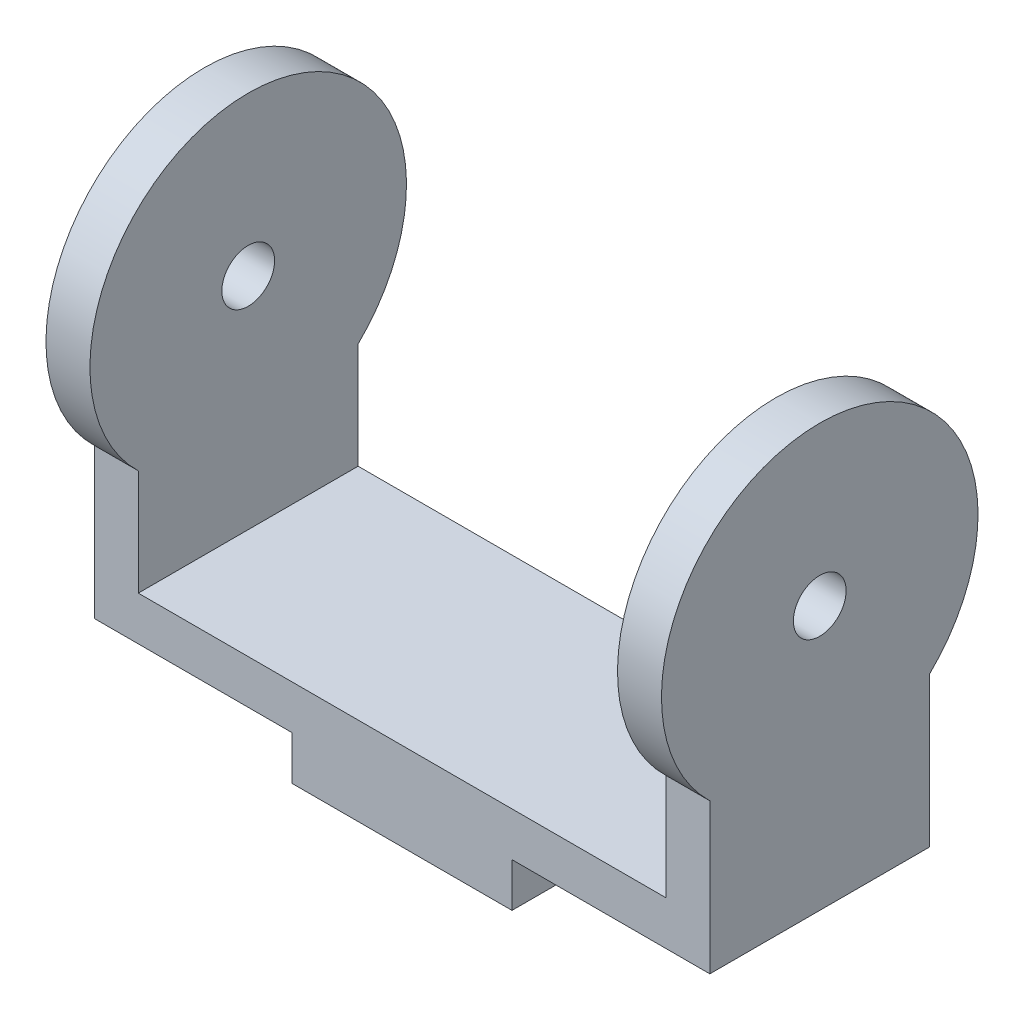
SolidWorks part; units mm, degrees
material "1060 Alloy"
ref_plane "Front Plane" through (0, 0, 0) normal (0, 0, 1) x (1, 0, 0)
ref_plane "Top Plane" through (0, 0, 0) normal (0, 1, 0) x (1, 0, 0)
ref_plane "Right Plane" through (0, 0, 0) normal (1, 0, 0) x (0, 0, -1)
sketch "Sketch1" plane through (0, 0, 0) normal (0, 1, 0) x (1, 0, 0)
  line L1 (0, 12.5) -> (35, 12.5)
  line L2 (0, 12.5) -> (0, -12.5)
  line L3 (0, -12.5) -> (35, -12.5)
  line L4 (35, 12.5) -> (35, -12.5)
  dimension "D1" = 25
  dimension "D2" = 35
  dimension "D3" = 0
extrude "Boss-Extrude1" add sketch "Sketch1" along normal blind 5
sketch "Sketch7" plane through (35, 0, 0) normal (1, 0, 0) x (0, 0, -1)
  line L0 (-12.5, 5) -> (-12.5, 17.0482)
  line L1 (-12.5, 5) -> (12.5, 5)
  line L2 (12.5, 5) -> (12.5, 17.0482)
  circle A0 centre (0, 30) radius 18
  arc A1 (-12.5, 17.0482) -> (12.5, 17.0482) centre (0, 30) ccw
  circle A2 centre (0, 30) radius 3
  line M4 (12.5, 5) -> (-12.5, 5)
  dimension "D1" = 30
extrude "Boss-Extrude2" add sketch "Sketch7" against normal blind 5 contours A0 A2 | A0 L0 L2 M4
mirror "Mirror1" about plane through (0, 5, -12.5) normal (1, 0, 0) of "Boss-Extrude1", "Boss-Extrude2"
sketch "Sketch8" plane through (0, 0, 0) normal (0, -1, 0) x (1, 0, 0)
  line L0 (35, -12.5) -> (-35, -12.5) construction
  line L1 (-12.5, 12.5) -> (12.5, 12.5)
  line L2 (-12.5, 12.5) -> (-12.5, -12.5)
  line L3 (-12.5, -12.5) -> (12.5, -12.5)
  line L4 (12.5, 12.5) -> (12.5, -12.5)
  line L5 (-12.5, 12.5) -> (12.5, -12.5) construction
  line L6 (-12.5, -12.5) -> (12.5, 12.5) construction
  line L7 (-35, 12.5) -> (-35, -12.5) construction
  point P0 (0, 0)
  dimension "D1" = 25
  dimension "D2" = 22.5
  dimension "D3" = 12.5
extrude "Boss-Extrude3" add sketch "Sketch8" along normal blind 5
